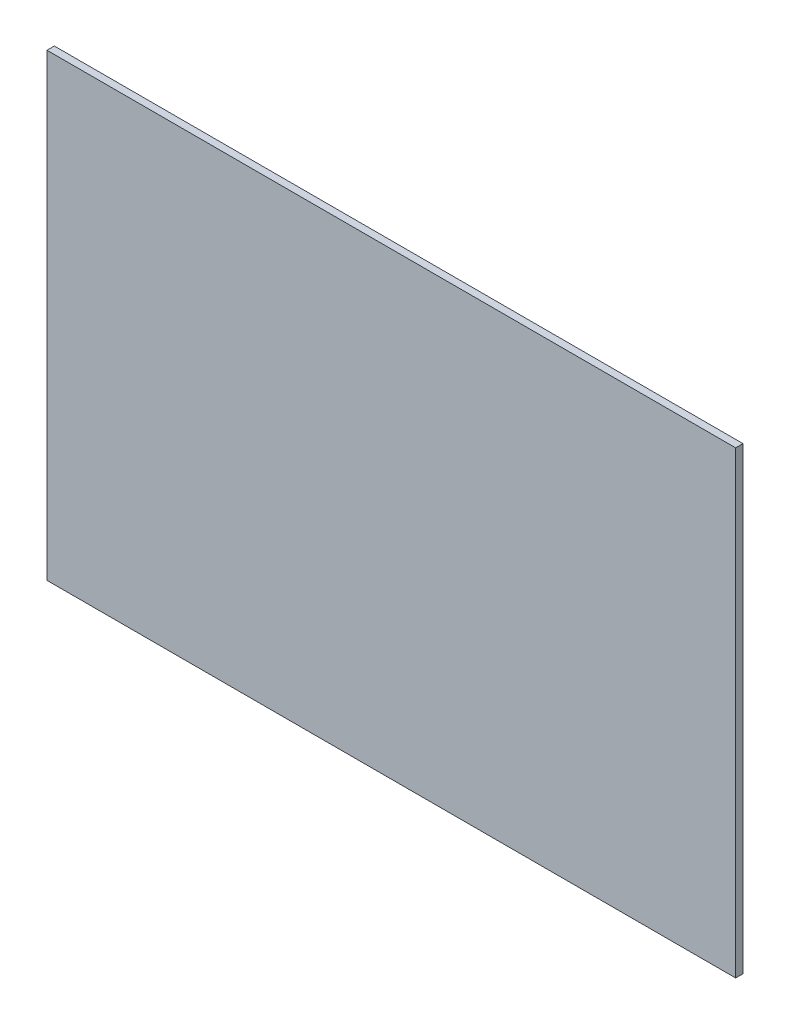
SolidWorks part; units mm, degrees
ref_plane "正面" through (0, 0, 0) normal (0, 0, 1) x (1, 0, 0)
ref_plane "平面" through (0, 0, 0) normal (0, 1, 0) x (1, 0, 0)
ref_plane "右側面" through (0, 0, 0) normal (1, 0, 0) x (0, 0, -1)
sketch "ｽｹｯﾁ1" plane through (0, 0, 0) normal (0, 0, 1) x (1, 0, 0)
  line L1 (-73.8944, 61.9929) -> (76.1056, 61.9929)
  line L2 (-73.8944, 61.9929) -> (-73.8944, -38.0071)
  line L3 (-73.8944, -38.0071) -> (76.1056, -38.0071)
  line L4 (76.1056, 61.9929) -> (76.1056, -38.0071)
  dimension "D3" = 100
  dimension "D4" = 150
extrude "ﾎﾞｽ - 押し出し1" add sketch "ｽｹｯﾁ1" along normal blind 1.6
